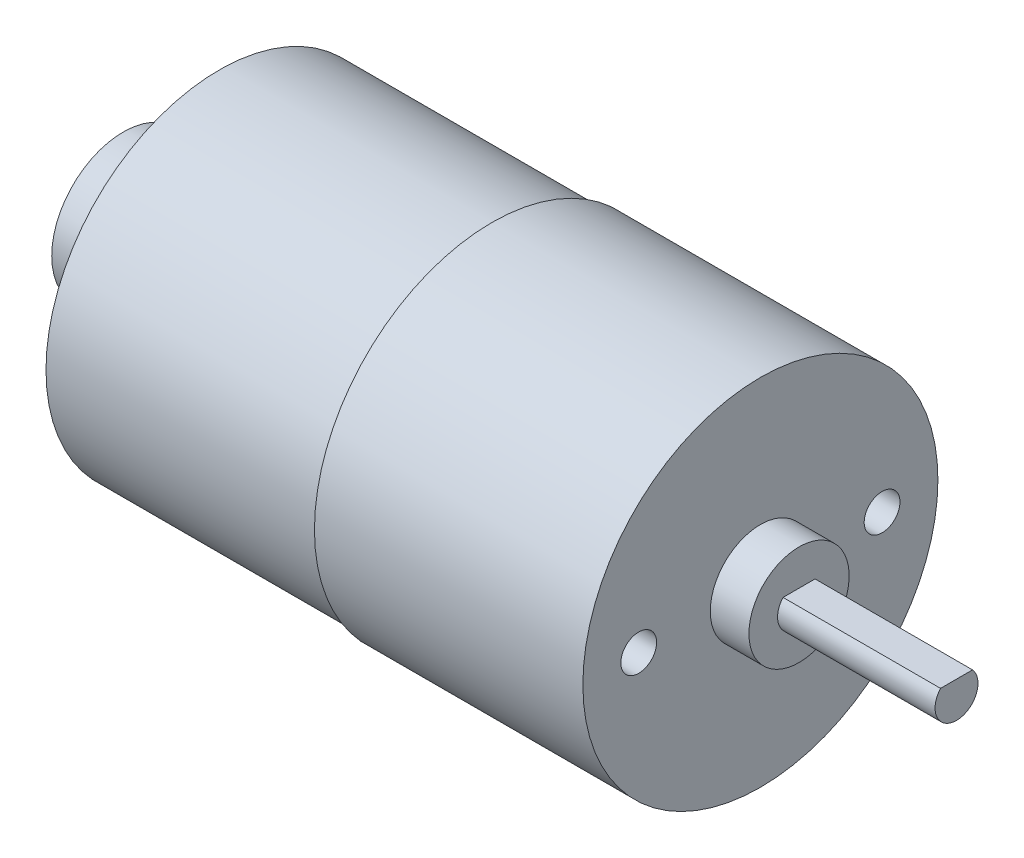
SolidWorks part; units mm, degrees
ref_plane "前视基准面" through (0, 0, 0) normal (0, 0, 1) x (1, 0, 0)
ref_plane "上视基准面" through (0, 0, 0) normal (0, 1, 0) x (1, 0, 0)
ref_plane "右视基准面" through (0, 0, 0) normal (1, 0, 0) x (0, 0, -1)
other "Configuration Table"
sketch "草图1" plane through (0, 0, 0) normal (0, 0, 1) x (1, 0, 0)
  line L0 (0, 0) -> (51.5, 0) construction
  line L1 (0, 0) -> (0, 12.1)
  line L2 (0, 12.1) -> (19.05, 12.1)
  line L3 (19.05, 12.1) -> (19.05, 12.4)
  line L4 (19.05, 12.4) -> (37.8, 12.4)
  line L5 (37.8, 12.4) -> (37.8, 3.5)
  line L6 (37.8, 3.5) -> (40.5, 3.5)
  line L7 (40.5, 3.5) -> (40.5, 1.5)
  line L8 (40.5, 1.5) -> (51.5, 1.5)
  line L9 (51.5, 1.5) -> (51.5, 0)
  line L10 (0, 0) -> (51.5, 0)
  dimension "D1" = 11
  dimension "D2" = 2.7
  dimension "D3" = 18.75
  dimension "D4" = 19.05
  dimension "D5" = 24.2
  dimension "D6" = 24.8
  dimension "D7" = 7
  dimension "D8" = 3
revolve "旋转1" add sketch "草图1" angle 360 about L0
sketch "草图2" plane through (0, 0, 0) normal (-1, 0, 0) x (0, 0, 1)
  circle A0 centre (0, 0) radius 5
  dimension "D1" = 10
extrude "凸台-拉伸1" add sketch "草图2" along normal blind 6.7
sketch "草图4" plane through (37.8, 0, 0) normal (1, 0, 0) x (0, 0, -1)
  line L0 (0, 15.1187) -> (0, -13.3927) construction
  line L1 (-15.5304, 0) -> (15.8135, 0) construction
  line L2 (-8.5, 6.4213) -> (-8.5, -5.6488) construction
  dimension "D1" = 8.5
hole_wizard "M3 螺纹孔的螺纹孔钻头1" positions "草图5" profile "草图6" hole size "M3" standard "GB"
sketch "草图5" plane through (37.8, 0, 0) normal (1, 0, 0) x (0, 0, -1)
  line L0 (-15.5304, 0) -> (15.8135, 0) construction
  line L1 (-8.5, 6.4213) -> (-8.5, -5.6488) construction
  point P0 (-8.5, 0)
sketch "草图6" plane through (37.8, 0, 8.5) normal (0, 1, 0) x (0, 0, -1)
  line L0 (0, 0) -> (0, 5)
  line L1 (0, 5) -> (1.25, 5)
  line L2 (1.25, 5) -> (1.25, 0)
  line L5 (1.25, 0) -> (0, 0)
  line L10 (0, 5) -> (-1.25, 5) construction
  line L11 (0, -6.35) -> (0, 107.95) construction
  dimension "孔直径" = 2.5
  dimension "孔深度" = 5
  dimension "导头角度" = 180
cosmetic thread "装饰螺纹线1" parameters "D2"=3.5
mirror "镜向1" about plane through (0, 0, 0) normal (0, 0, 1) of "M3 螺纹孔的螺纹孔钻头1"
sketch "草图7" plane through (51.5, 0, 0) normal (1, 0, 0) x (0, 0, -1)
  line L0 (-1.118, 1) -> (1.118, 1)
  circle A0 centre (0, 0) radius 1.5 construction
  circle A2 centre (0, 0) radius 1.5
  arc A3 (1.118, 1) -> (-1.118, 1) centre (0, 0) ccw
  point P4 (0.9766, 1.1385)
  dimension "D1" = 0
  dimension "D2" = 1
extrude "切除-拉伸1" cut sketch "草图7" against normal blind 11
equation "\"39.15mm-\"=39.15"
